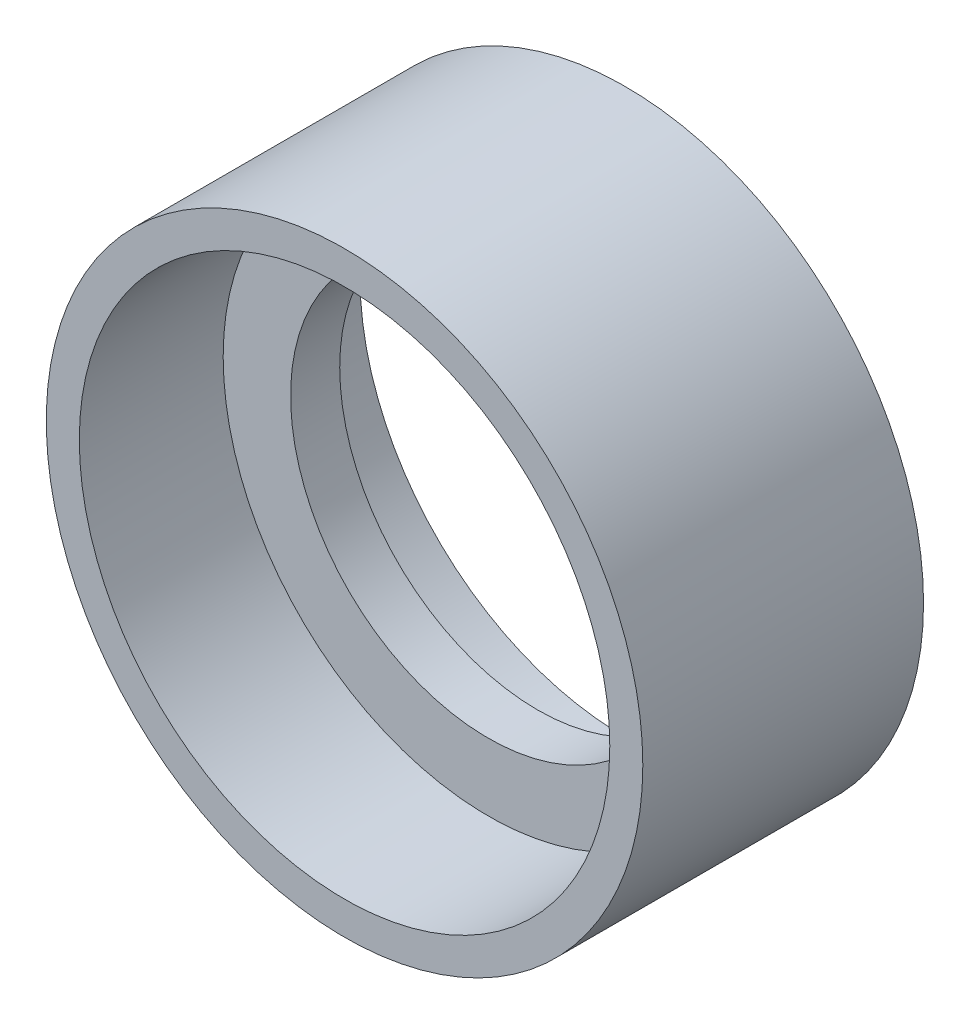
SolidWorks part; units mm, degrees
ref_plane "Front Plane" through (0, 0, 0) normal (0, 0, 1) x (1, 0, 0)
ref_plane "Top Plane" through (0, 0, 0) normal (0, 1, 0) x (1, 0, 0)
ref_plane "Right Plane" through (0, 0, 0) normal (1, 0, 0) x (0, 0, -1)
sketch "Sketch1" plane through (0, 0, 0) normal (0, 0, 1) x (1, 0, 0)
  circle A0 centre (0, 0) radius 13.4938
  dimension "D1" = 26.9875
extrude "Boss-Extrude1" add sketch "Sketch1" along normal blind 12.7
sketch "Sketch3" plane through (0, 0, 0) normal (0, 0, -1) x (-1, 0, 0)
  circle A0 centre (0, 0) radius 12
  dimension "D1" = 24
extrude "Cut-Extrude2" cut sketch "Sketch3" against normal through all
ref_plane "Plane1" through (0, 0, 3.9688) normal (0, 0, -1) x (-1, 0, 0)
sketch "Sketch4" plane through (0, 0, 3.9688) normal (0, 0, -1) x (-1, 0, 0)
  circle A1 centre (0, 0) radius 12
  dimension "D1" = 24
extrude "Boss-Extrude2" add sketch "Sketch4" against normal blind 2.2225
sketch "Sketch5" plane through (0, 0, 6.1913) normal (0, 0, 1) x (1, 0, 0)
  circle A0 centre (0, 0) radius 8.95
  dimension "D1" = 17.9
extrude "Cut-Extrude3" cut sketch "Sketch5" against normal through all
